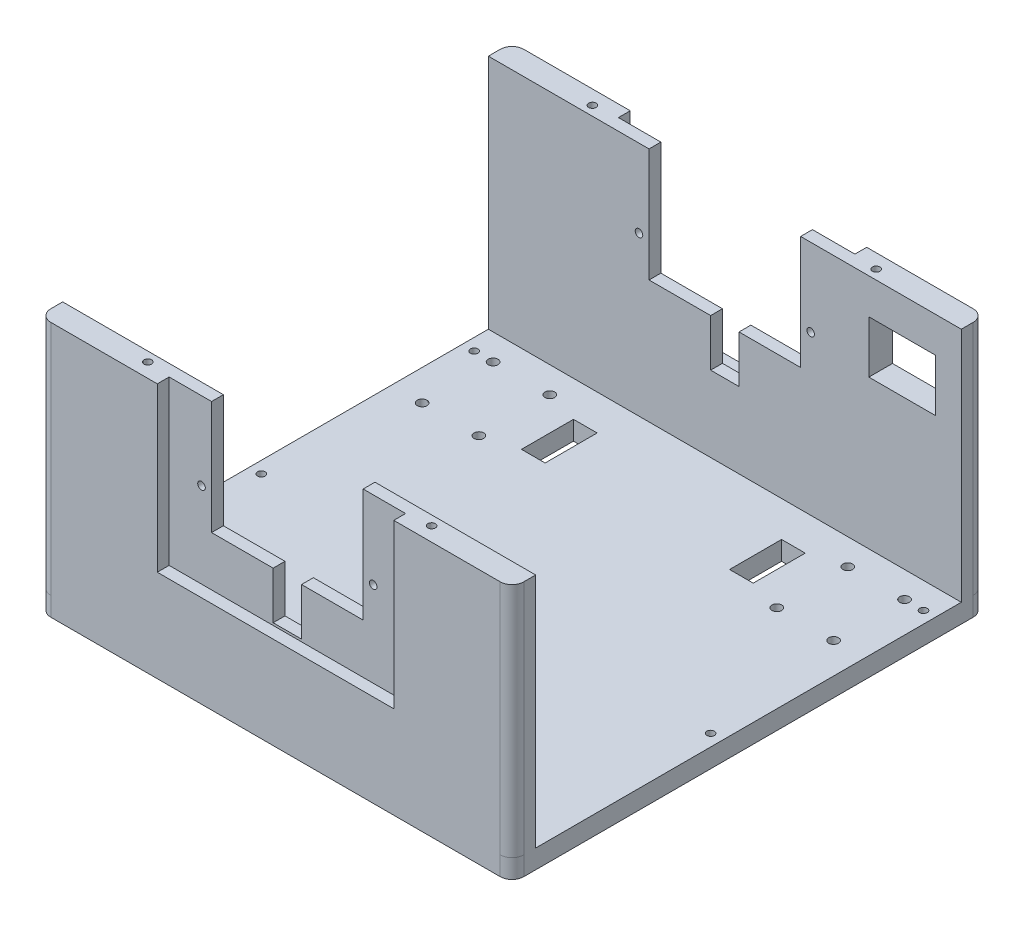
SolidWorks part; units mm, degrees
ref_plane "前视基准面" through (0, 0, 0) normal (0, 0, 1) x (1, 0, 0)
ref_plane "上视基准面" through (0, 0, 0) normal (0, 1, 0) x (1, 0, 0)
ref_plane "右视基准面" through (0, 0, 0) normal (1, 0, 0) x (0, 0, -1)
sketch "草图1" plane through (0, 0, 0) normal (0, 1, 0) x (1, 0, 0)
  line L0 (0, 100) -> (0, -100) construction
  line L1 (-100, 100) -> (100, 100)
  line L2 (-100, 100) -> (-100, -100)
  line L3 (-100, -100) -> (100, -100)
  line L4 (100, 100) -> (100, -100)
  line L5 (-100, 0) -> (100, 0) construction
  line L6 (49, 53) -> (39, 53)
  line L7 (-49, 75) -> (-39, 75)
  line L8 (-49, 75) -> (-49, 53)
  line L9 (-49, 53) -> (-39, 53)
  line L10 (-39, 75) -> (-39, 53)
  line L11 (39, 75) -> (39, 53)
  line L12 (49, 75) -> (39, 75)
  line L13 (49, 75) -> (49, 53)
  circle A1 centre (-87, 49) radius 2.05
  circle A2 centre (-63, 49) radius 2.05
  circle A3 centre (-63, 79) radius 2.05
  circle A4 centre (-87, 79) radius 2.05
  circle A5 centre (87, 49) radius 2.05
  circle A6 centre (63, 49) radius 2.05
  circle A7 centre (63, 79) radius 2.05
  circle A8 centre (87, 79) radius 2.05
  circle A9 centre (-95, 79) radius 1.6
  circle A10 centre (95, 79) radius 1.6
  circle A11 centre (95, -11) radius 1.6
  circle A12 centre (-95, -11) radius 1.6
  circle A14 centre (0, -22) radius 2.1
  circle A15 centre (0, -84) radius 2.1
  circle A16 centre (-22.5, -80) radius 2.1
  circle A17 centre (22.5, -80) radius 2.1
  dimension "D5" = 4.1
  dimension "D10" = 3.2
  dimension "D15" = 4.2
  dimension "D16" = 4.2
  dimension "D23" = 4.2
  dimension "D1" = 200
  dimension "D2" = 200
  dimension "D3" = 100
  dimension "D4" = 100
  dimension "D8" = 13
  dimension "D9" = 21
  dimension "D13" = 5
  dimension "D14" = 21
  dimension "D17" = 62
  dimension "D18" = 11
  dimension "D19" = 10
  dimension "D20" = 22
  dimension "D21" = 25
  dimension "D22" = 51
  dimension "D24" = 22.5
  dimension "D25" = 20
  dimension "D6" = 2
  dimension "D7" = 2
  dimension "D11" = 2
  dimension "D12" = 2
extrude "凸台-拉伸1" add sketch "草图1" along normal blind 8
fillet "圆角1" radius 5 1 edges at (-100, 4, 100)
fillet "圆角2" radius 5 1 edges at (100, 4, 100)
fillet "圆角3" radius 5 1 edges at (100, 4, -100)
fillet "圆角4" radius 5 1 edges at (-100, 4, -100)
sketch "草图2" plane through (0, 8, 0) normal (0, 1, 0) x (1, 0, 0)
  line L0 (-95, -100) -> (95, -100) construction
  line L1 (100, -100) -> (-100, -100)
  line L2 (100, -100) -> (100, -90)
  line L3 (100, -90) -> (-100, -90)
  line L4 (-100, -100) -> (-100, -90)
  line L7 (100, -95) -> (100, 95) construction
  line L8 (100, 0) -> (-100, 0) construction
  line L9 (-100, 95) -> (-100, -95) construction
  line L10 (100, 90) -> (-100, 90)
  line L11 (-100, 100) -> (-100, 90)
  line L12 (100, 100) -> (-100, 100)
  line L13 (100, 100) -> (100, 90)
  dimension "D1" = 10
  dimension "D2" = 200
  dimension "D3" = 0
extrude "凸台-拉伸2" add sketch "草图2" along normal blind 100
fillet "圆角5" radius 5 1 edges at (100, 58, -100)
fillet "圆角6" radius 5 1 edges at (-100, 58, -100)
fillet "圆角7" radius 5 1 edges at (-100, 58, 100)
fillet "圆角8" radius 5 1 edges at (100, 58, 100)
sketch "草图3" plane through (0, 0, -100) normal (0, 0, -1) x (-1, 0, 0)
  line L0 (-100, 8) -> (-100, 108) construction
  line L1 (-32.05, 108) -> (32.05, 108)
  line L2 (-32.05, 108) -> (-32.05, 60)
  line L3 (-32.05, 60) -> (-6, 60)
  line L4 (32.05, 108) -> (32.05, 60)
  line L5 (-95, 0) -> (95, 0) construction
  line L6 (0, 108) -> (0, 60) construction
  line L7 (-6, 60) -> (-6, 40)
  line L8 (-6, 40) -> (6, 40)
  line L9 (6, 40) -> (6, 60)
  line L10 (6, 60) -> (32.05, 60)
  circle A0 centre (-36.3, 75.05) radius 1.6
  circle A1 centre (36.3, 75.05) radius 1.6
  dimension "D5" = 3.2
  dimension "D1" = 64.1
  dimension "D2" = 48
  dimension "D3" = 67.95
  dimension "D4" = 60
  dimension "D6" = 36.3
  dimension "D7" = 12
  dimension "D8" = 20
  dimension "D9" = 6
extrude "切除-拉伸1" cut sketch "草图3" against normal blind 1000
sketch "草图4" plane through (0, 0, -100) normal (0, 0, -1) x (-1, 0, 0)
  line L0 (-100, 8) -> (-100, 108) construction
  line L1 (-50, 108) -> (50, 108)
  line L2 (-50, 108) -> (-50, 39)
  line L3 (-50, 39) -> (50, 39)
  line L4 (50, 108) -> (50, 39)
  line L5 (-95, 108) -> (-32.05, 108) construction
  dimension "D1" = 100
  dimension "D2" = 69
  dimension "D3" = 50
  dimension "D4" = 0
extrude "切除-拉伸2" cut sketch "草图4" against normal blind 5
mirror "镜向1" about plane through (0, 0, 0) normal (0, 0, 1) of "切除-拉伸2"
sketch "草图6" plane through (0, 108, 0) normal (0, 1, 0) x (1, 0, 0)
  line L0 (-100, 95) -> (-100, 90) construction
  line L4 (-50, 100) -> (-95, 100) construction
  circle A0 centre (-60, 94) radius 1.6
  circle A1 centre (60, 94) radius 1.6
  dimension "D1" = 3.2
  dimension "D2" = 40
  dimension "D3" = 6
  dimension "D4" = 120
extrude "切除-拉伸3" cut sketch "草图6" against normal blind 6
mirror "镜向2" about plane through (0, 0, 0) normal (0, 0, 1) of "切除-拉伸3"
sketch "草图7" plane through (0, 0, -100) normal (0, 0, -1) x (-1, 0, 0)
  line L0 (-95, 108) -> (-50, 108) construction
  line L1 (-89, 93) -> (-60.9, 93)
  line L2 (-89, 93) -> (-89, 70.9)
  line L3 (-89, 70.9) -> (-60.9, 70.9)
  line L4 (-60.9, 93) -> (-60.9, 70.9)
  line L5 (-100, 8) -> (-100, 108) construction
  dimension "D1" = 28.1
  dimension "D2" = 22.1
  dimension "D3" = 15
  dimension "D4" = 11
extrude "切除-拉伸4" cut sketch "草图7" against normal blind 100
